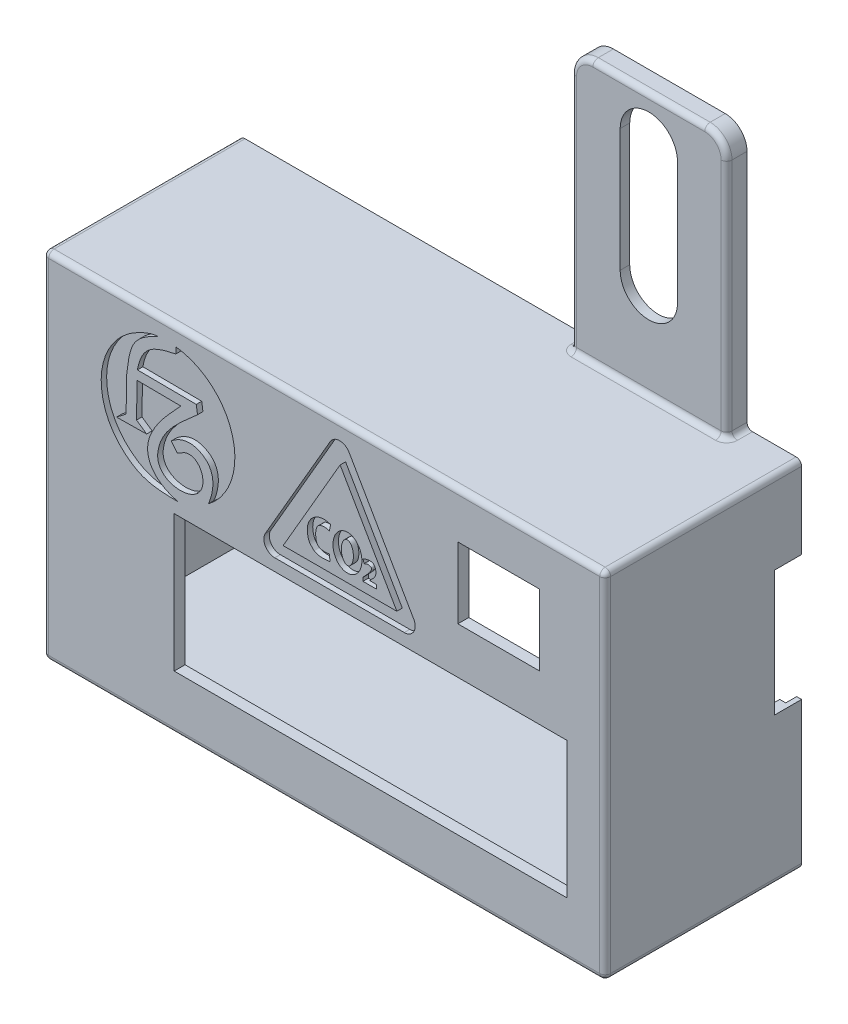
SolidWorks part; units mm, degrees
ref_plane "Front Plane" through (0, 0, 0) normal (0, 0, 1) x (1, 0, 0)
ref_plane "Top Plane" through (0, 0, 0) normal (0, 1, 0) x (1, 0, 0)
ref_plane "Right Plane" through (0, 0, 0) normal (1, 0, 0) x (0, 0, -1)
sketch "Croquis1" plane through (0, 0, 0) normal (0, 0, 1) x (1, 0, 0)
  line L1 (-51.5, 30.5) -> (51.5, 30.5)
  line L6 (-51.5, -34.5) -> (51.5, -34.5)
  line L9 (-51.5, 30.5) -> (-51.5, -34.5)
  line L10 (51.5, 30.5) -> (51.5, -34.5)
  point P1 (0, 0)
  dimension "D2" = 65
  dimension "D1" = 103
  dimension "D4" = 30.5
  dimension "D5" = 51.5
extrude "Saliente-Extruir2" add sketch "Croquis1" along normal blind 36
shell "Vaciado7" thickness 2
sketch "Croquis12" plane through (0, 0, 36) normal (0, 0, 1) x (1, 0, 0)
  line L1 (-27.5, 0.5) -> (44.5, 0.5)
  line L2 (-27.5, 0.5) -> (-27.5, -24.5)
  line L3 (-27.5, -24.5) -> (44.5, -24.5)
  line L4 (44.5, 0.5) -> (44.5, -24.5)
  line L5 (-27.5, 0.5) -> (44.5, -24.5) construction
  line L6 (-27.5, -24.5) -> (44.5, 0.5) construction
  line L7 (-51.5, -34.5) -> (51.5, -34.5) construction
  line L8 (51.5, -34.5) -> (51.5, 30.5) construction
  point P0 (8.5, -12)
  dimension "D1" = 10
  dimension "D2" = 72
  dimension "D3" = 25
  dimension "D4" = 7
extrude "Cortar-Extruir28" cut sketch "Croquis12" against normal up to next
sketch "Croquis29" plane through (0, 0, 0) normal (0, 0, -1) x (-1, 0, 0)
  line L9 (-13, 74.5) -> (-13, 30.5)
  line L10 (-17, 78.5) -> (-37.5, 78.5)
  line L12 (-51.5, 30.5) -> (51.5, 30.5) construction
  line L13 (-41.5, 30.5) -> (-13, 30.5)
  line L14 (-27.25, 70.25) -> (-27.25, 47.75) construction
  line L15 (-22, 70.25) -> (-22, 47.75)
  line L16 (-32.5, 70.25) -> (-32.5, 47.75)
  line L17 (-41.5, 30.5) -> (-41.5, 74.5)
  line L19 (-51.5, -34.5) -> (-51.5, 30.5) construction
  arc A8 (-22, 70.25) -> (-32.5, 70.25) centre (-27.25, 70.25) ccw
  arc A9 (-32.5, 47.75) -> (-22, 47.75) centre (-27.25, 47.75) ccw
  arc A10 (-41.5, 74.5) -> (-37.5, 78.5) centre (-37.5, 74.5) cw
  arc A11 (-13, 74.5) -> (-17, 78.5) centre (-17, 74.5) ccw
  point P2 (-27.25, 59)
  dimension "D3" = 10
  dimension "D4" = 4
  dimension "D7" = 5.25
  dimension "D2" = 4
  dimension "D1" = 28.5
  dimension "D5" = 48
  dimension "D6" = 22.5
  dimension "D8" = 14.25
  dimension "D9" = 8.25
extrude "Saliente-Extruir3" add sketch "Croquis29" against normal blind 3.75
sketch "Croquis14" plane through (0, 0, 0) normal (0, 0, -1) x (-1, 0, 0)
  line L8 (50.6, -33.6) -> (50.6, 29.6)
  line L10 (50.6, -33.6) -> (50.6, 29.6)
  line L12 (50.6, 29.6) -> (-13.9, 29.6)
  line L14 (50.6, 29.6) -> (-13.9, 29.6)
  line L16 (-13.9, 29.6) -> (-13.9, 74.5)
  line L17 (-13.9, 29.6) -> (-13.9, 74.5)
  line L18 (-17, 77.6) -> (-37.5, 77.6)
  line L19 (-17, 77.6) -> (-37.5, 77.6)
  line L20 (-40.6, 74.5) -> (-40.6, 29.6)
  line L21 (-40.6, 74.5) -> (-40.6, 29.6)
  line L22 (-40.6, 29.6) -> (-50.6, 29.6)
  line L23 (-40.6, 29.6) -> (-50.6, 29.6)
  line L28 (-50.6, 29.6) -> (-50.6, -33.6)
  line L29 (-50.6, 29.6) -> (-50.6, -33.6)
  line L30 (-50.6, -33.6) -> (50.6, -33.6)
  line L31 (-50.6, -33.6) -> (50.6, -33.6)
  arc A2 (-13.9, 74.5) -> (-17, 77.6) centre (-17, 74.5) ccw
  arc A4 (-13.9, 74.5) -> (-17, 77.6) centre (-17, 74.5) ccw
  arc A9 (-37.5, 77.6) -> (-40.6, 74.5) centre (-37.5, 74.5) ccw
  arc A10 (-37.5, 77.6) -> (-40.6, 74.5) centre (-37.5, 74.5) ccw
  dimension "D1" = 0.9
extrude "Cortar-Extruir11" cut sketch "Croquis14" against normal blind 2
sketch "Croquis16" plane through (-51.5, 0, 0) normal (-1, 0, 0) x (0, 0, 1)
  line L1 (2, -4.75) -> (12, -4.75)
  line L2 (2, -4.75) -> (2, -16.75)
  line L3 (2, -16.75) -> (12, -16.75)
  line L4 (12, -4.75) -> (12, -16.75)
  line L5 (2, -4.75) -> (12, -16.75) construction
  line L6 (2, -16.75) -> (12, -4.75) construction
  line L14 (36, -34.5) -> (0, -34.5) construction
  line L15 (0, 30.5) -> (0, -34.5) construction
  point P0 (7, -10.75)
  dimension "D1" = 2
  dimension "D2" = 23.75
  dimension "D3" = 12
  dimension "D4" = 10
extrude "Cortar-Extruir17" cut sketch "Croquis16" against normal up to next
sketch "Croquis19" plane through (0, 0, 36) normal (0, 0, 1) x (1, 0, 0)
  line L0 (105.4121, 47.0931) -> (337.4121, 47.0931) construction
  line L1 (-36.2237, 18.1032) -> (-36.3002, 11.9067)
  line L2 (-36.3002, 11.9067) -> (-38.0597, 10.5297)
  line L3 (-38.0597, 10.5297) -> (-32.5517, 10.6062)
  line L4 (-32.5517, 10.6062) -> (-34.3877, 11.9067)
  line L5 (-34.3877, 11.9067) -> (-34.3112, 18.2562)
  line L6 (-34.3112, 18.2562) -> (-26.2787, 18.1797)
  line L9 (-23.2187, 18.3327) -> (-23.4482, 19.8627)
  line L10 (-23.4482, 19.8627) -> (-34.2347, 19.9392)
  line L11 (-27.1967, 25.9827) -> (-27.1967, 27.1302)
  line L12 (-28.0382, 11.7537) -> (-26.8907, 10.3767)
  arc A0 (-27.1967, 27.1302) -> (-21.2297, 5.1747) centre (-28.6325, 14.9514) cw
  spline S0 degree 3 poles (-26.8142, 2.7267) (-31.0337, 2.8063) (-33.7222, 2.8984) (-36.9887, 5.9397) (-38.3461, 7.2035) (-39.4996, 8.931) (-40.1252, 10.6827) (-41.9717, 15.8528) (-40.3364, 21.4131) (-35.9942, 24.7587) (-34.7774, 25.6963) (-32.0434, 27.1302) (-30.4862, 27.1302) knots 0 0 0 0 1 1 1 2 2 2 3 3 3 4 4 4 4
  spline S1 degree 3 poles (-30.4862, 27.1302) (-35.2764, 24.8948) (-35.6335, 23.1795) (-36.2237, 18.1032) knots 0 0 0 0 1 1 1 1
  spline S2 degree 3 poles (-26.2787, 18.1797) (-28.2237, 16.0186) (-30.378, 13.917) (-31.6337, 11.2947) (-33.7314, 6.9143) (-31.0663, 3.7898) (-26.8142, 2.7267) knots 0 0 0 0 1 1 1 2 2 2 2
  spline S3 degree 3 poles (-21.2297, 5.1747) (-20.0822, 7.887) (-19.6473, 11.4696) (-23.1422, 12.8247) (-24.9644, 13.5313) (-26.6747, 12.9075) (-28.0382, 11.7537) knots 0 0 0 0 1 1 1 2 2 2 2
  spline S4 degree 3 poles (-26.8907, 10.3767) (-26.3552, 10.6572) (-25.8733, 11.0823) (-25.2842, 11.2182) (-22.4033, 11.8831) (-20.9421, 7.2589) (-23.6777, 5.4807) (-26.2196, 3.8285) (-31.0119, 4.9403) (-30.4862, 8.7702) (-29.8977, 13.0583) (-26.1484, 15.6284) (-23.2187, 18.3327) knots 0 0 0 0 1 1 1 2 2 2 3 3 3 4 4 4 4
  spline S5 degree 3 poles (-34.2347, 19.9392) (-33.4577, 24.135) (-31.48, 25.1261) (-27.1967, 25.9827) knots 0 0 0 0 1 1 1 1
extrude "Cortar-Extruir18" cut sketch "Croquis19" against normal blind 1
sketch "Croquis30" plane through (0, 0, 36) normal (0, 0, 1) x (1, 0, 0)
  line L1 (24.5, 22) -> (39.5, 22)
  line L2 (24.5, 22) -> (24.5, 9)
  line L3 (24.5, 9) -> (39.5, 9)
  line L4 (39.5, 22) -> (39.5, 9)
  line L5 (51.5, -34.5) -> (51.5, 30.5) construction
  line L7 (51.5, 30.5) -> (-51.5, 30.5) construction
  dimension "D1" = 15
  dimension "D2" = 13
  dimension "D3" = 12
  dimension "D4" = 8.5
extrude "Cortar-Extruir29" cut sketch "Croquis30" against normal up to next
sketch "Croquis20" plane through (0, 0, 36) normal (0, 0, 1) x (1, 0, 0)
  line L0 (-454.7792, 225.5349) -> (-56.1125, 225.5349) construction
  line L1 (1.17, 13.0916) -> (0.9579, 11.9781)
  line L2 (0.9579, 8.3197) -> (1.064, 7.1533)
  line L3 (8.3278, 7.7895) -> (9.6014, 7.7895)
  line L4 (9.6014, 7.7895) -> (9.6014, 7.0453)
  line L5 (9.6014, 7.0453) -> (7.1083, 7.0472)
  line L6 (7.3204, 9.9634) -> (7.1083, 10.5996)
  line L7 (2.9197, 23.4306) -> (13.315, 5.4036)
  line L8 (13.315, 5.4036) -> (-7.5253, 5.4036)
  line L9 (-7.5253, 5.4036) -> (2.9197, 23.4306)
  line L13 (4.5726, 26.237) -> (16.412, 5.7059)
  line L14 (14.6794, 2.7068) -> (-9.0559, 2.7068)
  line L15 (-10.7864, 5.7095) -> (1.1095, 26.2406)
  arc A0 (-9.0559, 2.7068) -> (-10.7864, 5.7095) centre (-9.0559, 4.7068) cw
  arc A1 (16.412, 5.7059) -> (14.6794, 2.7068) centre (14.6794, 4.7068) cw
  arc A2 (4.5726, 26.237) -> (1.1095, 26.2406) centre (2.84, 25.2379) ccw
  ellipse E0 centre (4.2612, 10.1768) end of major axis (4.2249, 6.9329) minor radius 2.6495
  ellipse E1 centre (4.2477, 10.1789) end of major axis (4.2725, 8.1494) minor radius 1.1049
  spline S0 degree 3 poles (1.064, 7.1533) (-0.0057, 7.0196) (-0.831, 6.9185) (-1.7991, 7.3654) (-1.8445, 7.3863) (-1.8698, 7.4361) (-1.9052, 7.4714) (-2.254, 7.8203) (-2.5563, 8.0351) (-2.7535, 8.4788) (-3.523, 10.2102) (-3.0167, 12.3549) (-1.2159, 13.0916) (-0.4348, 13.4111) (0.3944, 13.4018) (1.17, 13.0916) knots 0 0 0 0 1 1 1 2 2 2 3 3 3 4 4 4 5 5 5 5
  spline S1 degree 3 poles (0.9579, 11.9781) (0.7282, 12.0312) (0.5038, 12.1198) (0.2687, 12.1372) (0.0213, 12.1555) (-0.2277, 12.117) (-0.4736, 12.0842) (-1.7617, 11.9124) (-1.6802, 9.8231) (-1.375, 9.009) (-1.0213, 8.0659) (0.2108, 8.1952) (0.9579, 8.3197) knots 0 0 0 0 1 1 1 2 2 2 3 3 3 4 4 4 4
  spline S2 degree 3 poles (7.1083, 10.5996) (8.5526, 11.3218) (9.6743, 10.9693) (9.4412, 9.2211) (9.3807, 8.7669) (8.5844, 8.0694) (8.3278, 7.7895) knots 0 0 0 0 1 1 1 2 2 2 2
  spline S3 degree 3 poles (7.1083, 7.0472) (7.126, 7.277) (7.0706, 7.5247) (7.1614, 7.7365) (7.2647, 7.9775) (9.8444, 10.1754) (8.0097, 10.1754) (7.6404, 10.1754) (7.6267, 10.0399) (7.3204, 9.9634) knots 0 0 0 0 1 1 1 2 2 2 3 3 3 3
  dimension "D1" = 2
extrude "Cortar-Extruir24" cut sketch "Croquis20" against normal blind 1 contours L13 A2 L15 A0 L14 A1 L8 L9 L7 | S1 L1 S0 L2 | E0 E1 | S3 L5 L4 L3 S2 L6
sketch "Croquis31" plane through (51.5, 0, 0) normal (1, 0, 0) x (0, 0, -1)
  line L0 (0, -34.5) -> (0, 30.5) construction
  line L1 (0, 15.5) -> (-5, 15.5)
  line L2 (0, 15.5) -> (0, -7.5)
  line L3 (0, -7.5) -> (-5, -7.5)
  line L4 (-5, 15.5) -> (-5, -7.5)
  line L5 (-36, 30.5) -> (0, 30.5) construction
  dimension "D1" = 5
  dimension "D2" = 23
  dimension "D3" = 15
extrude "Cortar-Extruir30" cut sketch "Croquis31" against normal up to next
fillet "Redondeo1" radius 1 16 edges at (13, 30.5, 1.875) (41.5, 30.5, 1.875) (13, 52.5, 3.75) (14.1716, 77.3284, 3.75) (27.25, 78.5, 3.75) (40.3284, 77.3284, 3.75) (27.25, 30.5, 3.75) (41.5, 52.5, 3.75) (-51.5, 30.5, 18) (-51.5, -2, 36) (-51.5, -34.5, 18) (51.5, -34.5, 18) (0, -34.5, 36) (51.5, -2, 36) (51.5, 30.5, 18) (0, 30.5, 36)
